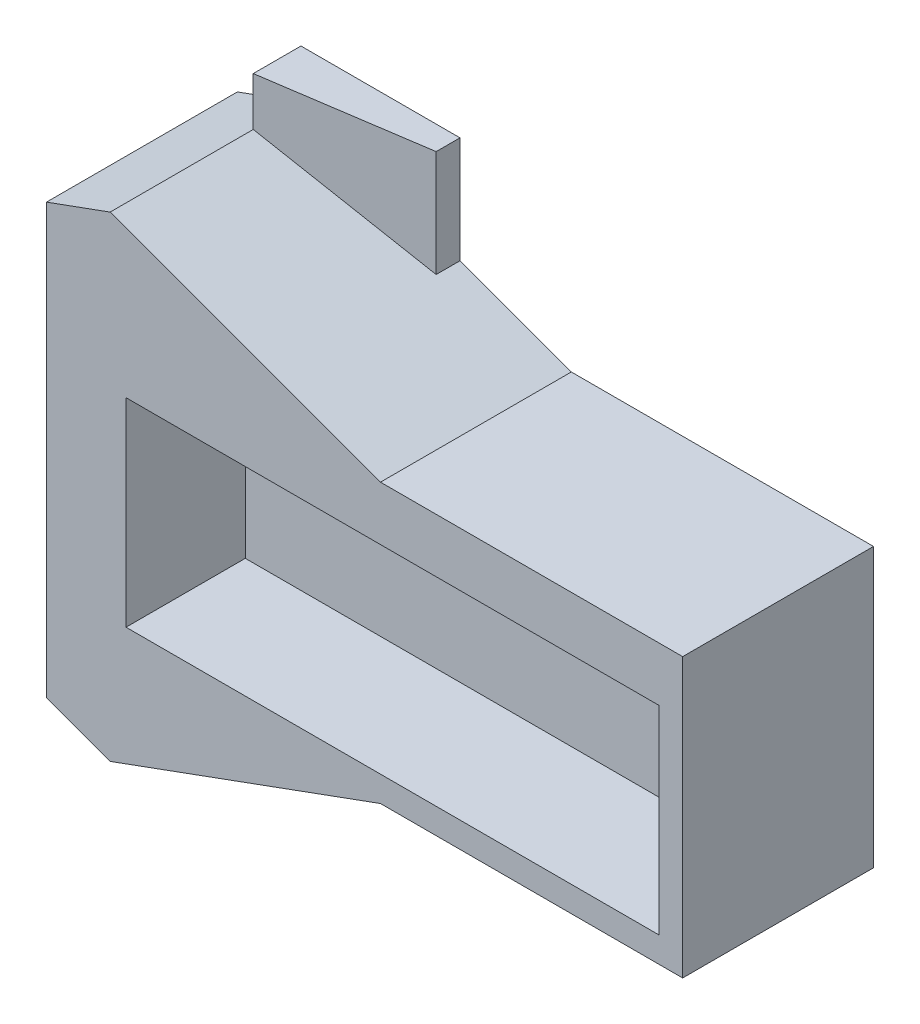
SolidWorks part; units mm, degrees
ref_plane "Front Plane" through (0, 0, 0) normal (0, 0, 1) x (1, 0, 0)
ref_plane "Top Plane" through (0, 0, 0) normal (0, 1, 0) x (1, 0, 0)
ref_plane "Right Plane" through (0, 0, 0) normal (1, 0, 0) x (0, 0, -1)
sketch "Sketch1" plane through (0, 0, 0) normal (0, 0, 1) x (1, 0, 0)
  line L0 (-964.1278, 0) -> (47242.2604, 0) construction
  line L1 (0, -27) -> (0, 27)
  line L2 (0, 27) -> (8, 29.9118)
  line L3 (8, 29.9118) -> (42, 17.5)
  line L4 (42, 17.5) -> (80, 17.5)
  line L5 (80, 17.5) -> (80, -17.5)
  line L6 (42, -17.5) -> (80, -17.5)
  line L7 (8, -29.9118) -> (42, -17.5)
  line L8 (0, -27) -> (8, -29.9118)
  point P10 (80, 0)
  point P13 (0, 0)
  dimension "D1" = 27
  dimension "D2" = 8
  dimension "D3" = 38
  dimension "D4" = 70
  dimension "D5" = 80
  dimension "D6" = 17.5
extrude "Boss-Extrude1" add sketch "Sketch1" along normal blind 24
sketch "Sketch2" plane through (0, 0, 0) normal (0, 1, 0) x (1, 0, 0)
  line L0 (8, 0) -> (8, -6)
  line L1 (8, -24) -> (8, 0) construction
  line L2 (8, -6) -> (28, -3)
  line L3 (28, -3) -> (28, 0)
  line L4 (8, 0) -> (42, 0) construction
  line L5 (28, 0) -> (8, 0)
  line L6 (0, -24) -> (0, 0) construction
  dimension "D1" = 20
  dimension "D2" = 3
  dimension "D3" = 6
  dimension "D4" = 8
extrude "Boss-Extrude2" add sketch "Sketch2" along normal mid plane 72
sketch "Sketch3" plane through (0, 0, 24) normal (0, 0, 1) x (1, 0, 0)
  line L0 (-994.6244, -1.7978) -> (49005.3756, -1.7978) construction
  line L1 (80, -17.5) -> (80, 17.5) construction
  line L2 (10, -14.2978) -> (77, -14.2978)
  line L3 (10, -14.2978) -> (10, 10.7022)
  line L4 (10, 10.7022) -> (77, 10.7022)
  line L5 (77, -14.2978) -> (77, 10.7022)
  line L6 (10, -14.2978) -> (77, 10.7022) construction
  line L7 (10, 10.7022) -> (77, -14.2978) construction
  point P1 (43.5, -1.7978)
  dimension "D1" = 67
  dimension "D2" = 3
  dimension "D3" = 25
extrude "Cut-Extrude2" cut sketch "Sketch3" against normal blind 15
